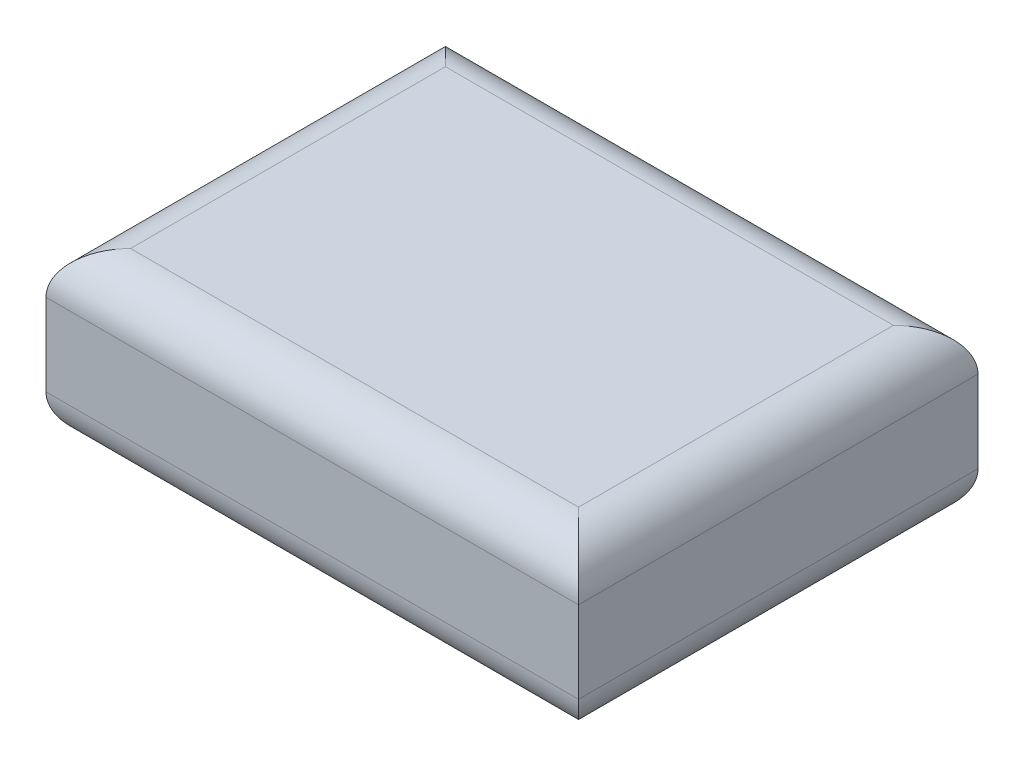
SolidWorks part; units mm, degrees
ref_plane "Front Plane" through (0, 0, 0) normal (0, 0, 1) x (1, 0, 0)
ref_plane "Top Plane" through (0, 0, 0) normal (0, 1, 0) x (1, 0, 0)
ref_plane "Right Plane" through (0, 0, 0) normal (1, 0, 0) x (0, 0, -1)
sketch "Sketch1" plane through (0, 0, 0) normal (0, 0, 1) x (1, 0, 0)
  line L1 (0, 0) -> (16, 0)
  line L2 (0, 0) -> (0, 5)
  line L3 (0, 5) -> (16, 5)
  line L4 (16, 0) -> (16, 5)
  dimension "D1" = 5
  dimension "D2" = 16
extrude "Boss-Extrude1" add sketch "Sketch1" along normal blind 12
fillet "Fillet3" radius 1.27 8 edges at (16, 5, 6) (8, 0, 0) (0, 0, 6) (8, 0, 12) (16, 0, 6) (8, 5, 12) (8, 5, 0) (0, 5, 6)
